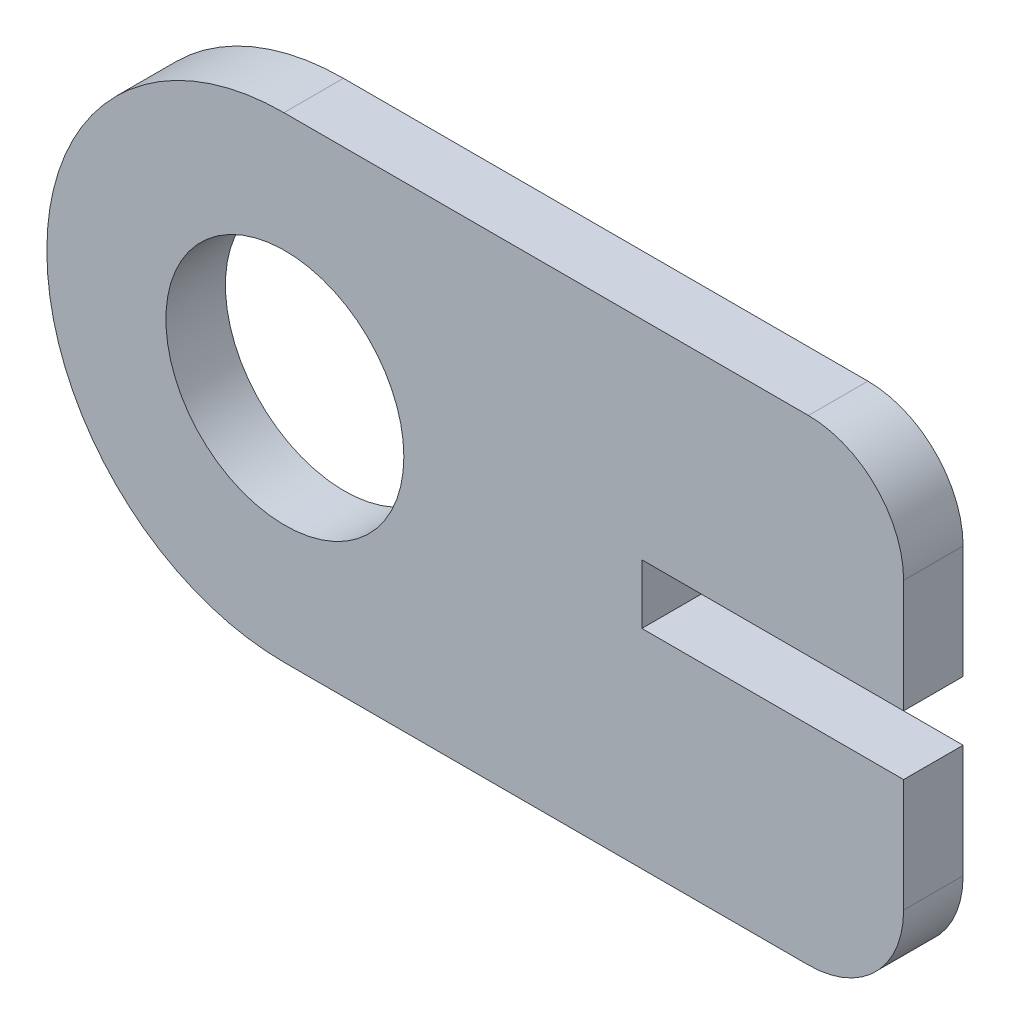
SolidWorks part; units mm, degrees
material "E-Glass Fiber"
ref_plane "Front Plane" through (0, 0, 0) normal (0, 0, 1) x (1, 0, 0)
ref_plane "Top Plane" through (0, 0, 0) normal (0, 1, 0) x (1, 0, 0)
ref_plane "Right Plane" through (0, 0, 0) normal (1, 0, 0) x (0, 0, -1)
sketch "Sketch1" plane through (0, 0, 0) normal (0, 0, 1) x (1, 0, 0)
  line L0 (-3.175, 0) -> (3.175, 0) construction
  line L1 (-0.0254, 6.35) -> (13.97, 6.35)
  line L2 (-6.35, 0.0254) -> (-6.35, -0.0254)
  line L3 (-0.0254, -6.35) -> (13.97, -6.35)
  line L4 (16.51, 3.81) -> (16.51, 0.7937)
  line L5 (16.51, -0.7937) -> (16.51, -3.81)
  line L6 (16.51, 0.7937) -> (9.525, 0.7937)
  line L8 (16.51, -0.7937) -> (9.525, -0.7937)
  line L9 (9.525, 0.7937) -> (9.525, -0.7937)
  circle A0 centre (0, 0) radius 3.175
  circle A1 centre (38.1, 0) radius 47.9425 construction
  arc A2 (13.97, -6.35) -> (16.51, -3.81) centre (13.97, -3.81) ccw
  arc A3 (13.97, 6.35) -> (16.51, 3.81) centre (13.97, 3.81) cw
  arc A4 (-6.35, -0.0254) -> (-0.0254, -6.35) centre (-0.0254, -0.0254) ccw
  arc A5 (-0.0254, 6.35) -> (-6.35, 0.0254) centre (-0.0254, 0.0254) ccw
  point P21 (-6.35, -6.35)
  point P24 (-6.35, 6.35)
  dimension "D1" = 6.35
  dimension "D5" = 95.885
  dimension "D9" = 2.54
  dimension "D10" = 6.3246
  dimension "D2" = 12.7
  dimension "D3" = 6.35
  dimension "D4" = 16.51
  dimension "D6" = 38.1
  dimension "D7" = 1.5875
  dimension "D8" = 28.575
extrude "Boss-Extrude1" add sketch "Sketch1" along normal blind 1.5875
